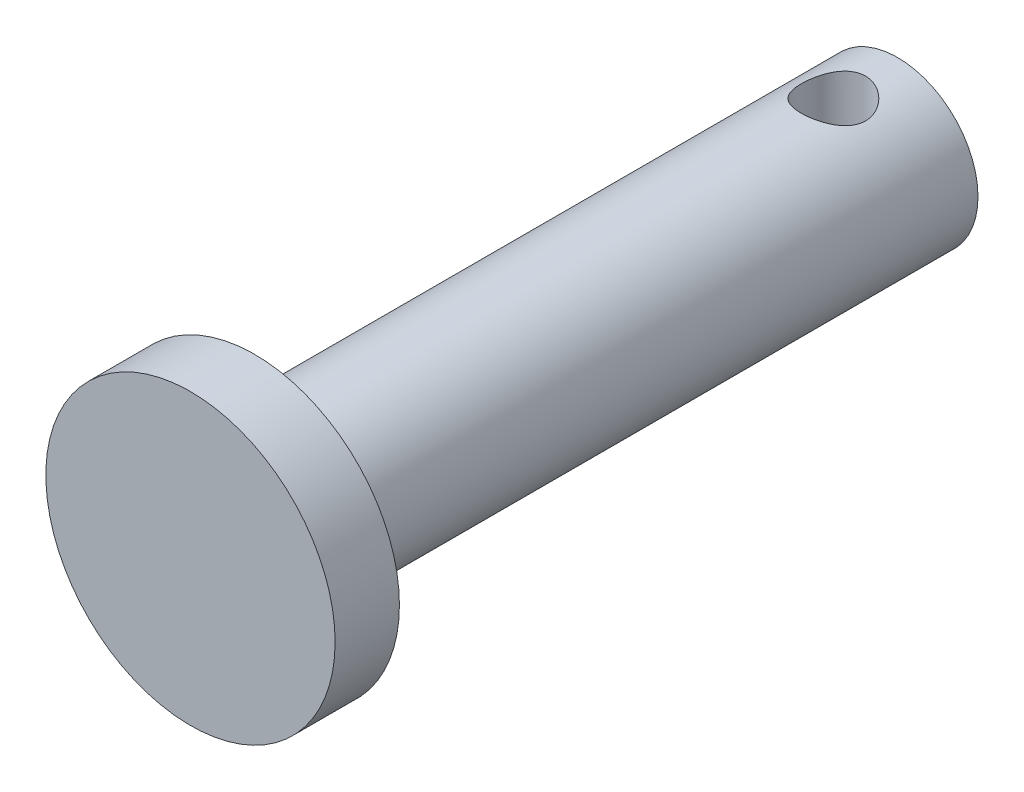
SolidWorks part; units mm, degrees
ref_plane "Front Plane" through (0, 0, 0) normal (0, 0, 1) x (1, 0, 0)
ref_plane "Top Plane" through (0, 0, 0) normal (0, 1, 0) x (1, 0, 0)
ref_plane "Right Plane" through (0, 0, 0) normal (1, 0, 0) x (0, 0, -1)
sketch "Sketch1" plane through (0, 0, 0) normal (0, 0, 1) x (1, 0, 0)
  circle A0 centre (0, 0) radius 2.5
  dimension "D1" = 5
extrude "Boss-Extrude1" add sketch "Sketch1" along normal blind 20
sketch "Sketch2" plane through (0, 0, 20) normal (0, 0, 1) x (1, 0, 0)
  circle A2 centre (0, 0) radius 4.5
  circle A3 centre (0, 0) radius 4.5
  dimension "D1" = 2
extrude "Boss-Extrude2" add sketch "Sketch2" along normal blind 2
sketch "Sketch3" plane through (0, 0, 0) normal (0, 1, 0) x (1, 0, 0)
  line L0 (2.5, -20) -> (2.5, 0) construction
  line L1 (2.5, 0) -> (-2.5, 0) construction
  circle A0 centre (0, -2) radius 1
  dimension "D1" = 2
  dimension "D2" = 2.5
  dimension "D3" = 2
extrude "Cut-Extrude1" cut sketch "Sketch3" against normal through all both and the other way through all
